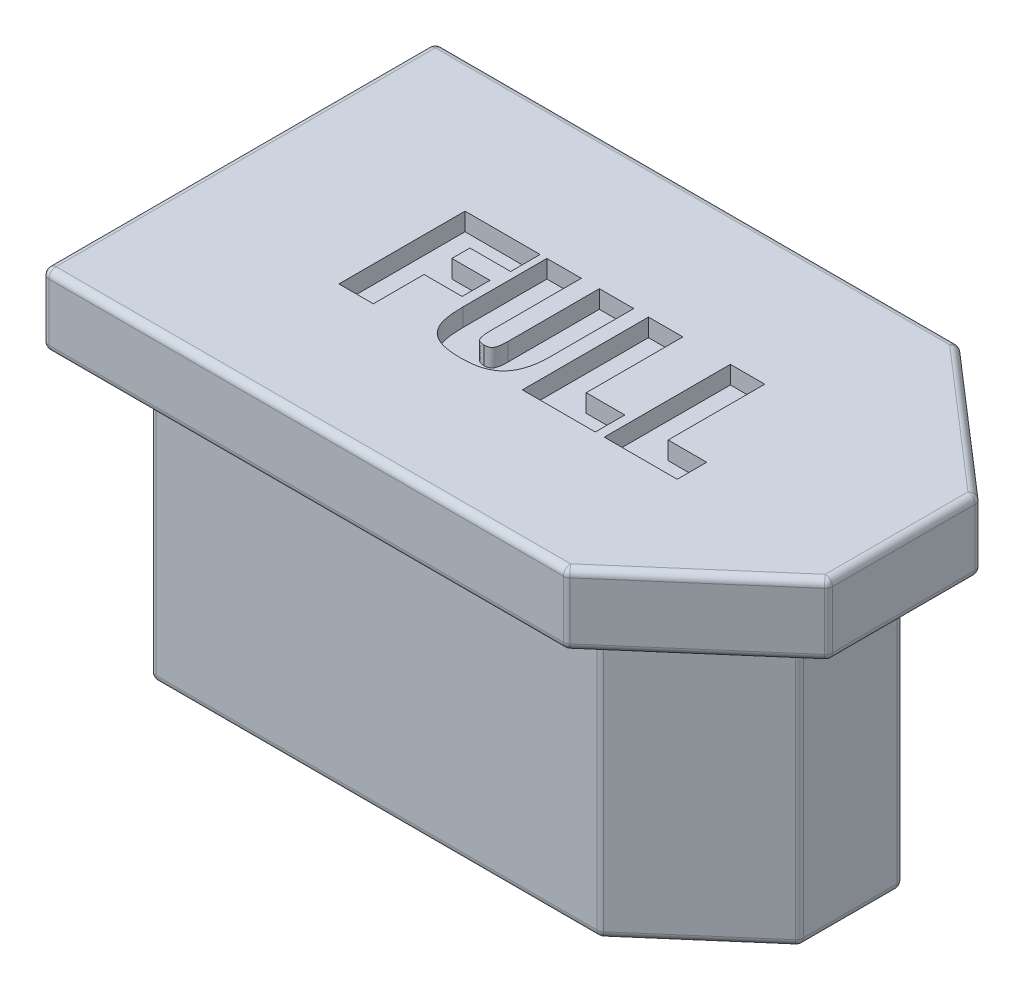
SolidWorks part; units mm, degrees
ref_plane "Front Plane" through (0, 0, 0) normal (0, 0, 1) x (1, 0, 0)
ref_plane "Top Plane" through (0, 0, 0) normal (0, 1, 0) x (1, 0, 0)
ref_plane "Right Plane" through (0, 0, 0) normal (1, 0, 0) x (0, 0, -1)
sketch "Sketch1" plane through (0, 0, 0) normal (0, 1, 0) x (1, 0, 0)
  line L0 (-7.8002, 4) -> (4.7998, 4)
  line L1 (4.7998, 4) -> (7.8002, 1.4)
  line L2 (7.8002, 1.4) -> (7.8002, -1.4)
  line L3 (7.8002, -1.4) -> (4.7998, -4)
  line L4 (4.7998, -4) -> (-7.8002, -4)
  line L5 (-7.8002, -4) -> (-7.8002, 4)
  line L6 (-7.8002, 0) -> (7.8002, 0) construction
  dimension "D1" = 8
  dimension "D2" = 12.6
  dimension "D3" = 139.09
  dimension "D4" = 2.8
extrude "Boss-Extrude1" add sketch "Sketch1" along normal mid plane 8
shell "Shell1" thickness 0.7
sketch "Sketch2" plane through (0, 4, 0) normal (0, 1, 0) x (1, 0, 0)
  line L0 (-7.8002, 4) -> (-7.8002, -4) construction
  line L1 (4.7998, 4) -> (-7.8002, 4) construction
  line L2 (7.8002, 1.4) -> (4.7998, 4) construction
  line L3 (7.8002, -1.4) -> (7.8002, 1.4) construction
  line L4 (4.7998, -4) -> (7.8002, -1.4) construction
  line L5 (-7.8002, -4) -> (4.7998, -4) construction
  line L6 (-7.8002, 4) -> (-7.8002, -4) construction
  line L7 (4.7998, 4) -> (-7.8002, 4) construction
  line L8 (7.8002, 1.4) -> (4.7998, 4) construction
  line L9 (7.8002, -1.4) -> (7.8002, 1.4) construction
  line L10 (4.7998, -4) -> (7.8002, -1.4) construction
  line L11 (-7.8002, -4) -> (4.7998, -4) construction
  line L12 (-9.3002, 5.5) -> (-9.3002, -5.5)
  line L13 (-9.3002, -5.5) -> (5.3593, -5.5)
  line L14 (5.3593, -5.5) -> (9.3002, -2.085)
  line L15 (9.3002, -2.085) -> (9.3002, 2.085)
  line L16 (9.3002, 2.085) -> (5.3593, 5.5)
  line L17 (5.3593, 5.5) -> (-9.3002, 5.5)
  dimension "D1" = 1.5
extrude "Boss-Extrude2" add sketch "Sketch2" along normal blind 2
sketch "Sketch4" plane through (0, -4, 0) normal (0, -1, 0) x (1, 0, 0)
  line L0 (-1.1002, -3.3) -> (-1.1002, -2.1)
  line L3 (4.5387, -3.3) -> (-7.1002, -3.3) construction
  line L5 (-1.1002, -2.1) -> (0.8998, -2.1)
  line L6 (0.8998, -2.1) -> (0.8998, -3.3)
  line L7 (-1.1002, -3.3) -> (0.8998, -3.3)
  dimension "D1" = 1.2
  dimension "D2" = 2
  dimension "D3" = 6
extrude "Boss-Extrude4" add sketch "Sketch4" against normal up to next
sketch "Sketch5" plane through (0, 4, 0) normal (0, -1, 0) x (1, 0, 0)
  line L0 (-0.6502, -2.1) -> (-0.6502, 1.9)
  line L1 (0.8998, -2.1) -> (-1.1002, -2.1) construction
  line L2 (-0.6502, 1.9) -> (0.4498, 1.9)
  line L3 (0.4498, 1.9) -> (0.4498, -2.1)
  line L4 (0.8998, -2.1) -> (-1.1002, -2.1) construction
  line L5 (0.4498, -2.1) -> (-0.6502, -2.1)
  line L6 (-0.1002, -2.1) -> (-0.1002, 1.9) construction
  dimension "D1" = 4
  dimension "D2" = 1.1
extrude "Cut-Extrude1" cut sketch "Sketch5" against normal blind 1
fillet "Fillet1" radius 0.2 78 edges at (4.5387, 0, -3.3) (7.1002, 0, -1.0803) (7.1002, 0, 1.0803) (4.5387, 0, 3.3) (-7.1002, 0, -3.3) (-1.1002, 0, -3.3) (-1.1002, 0, -2.1) (0.8998, 0, -2.1) (0.8998, 0, -3.3) (-7.1002, 0, 3.3) (0.8998, 4, -2.7) (0.8998, -4, -2.7) (2.7192, -4, -3.3) (-1.1002, 4, -2.7) (-1.1002, -4, -2.7) (-0.1002, 4, 1.9) (5.8195, -4, -2.1902) (-4.1002, -4, -3.3) (-0.1002, -4, -2.1) (-0.1002, 5, 1.9) (0.4498, 4.5, 1.9) (-0.6502, 4.5, 1.9) (0.4498, 5, -0.1) (-0.6502, 5, -0.1) (5.8195, 4, -2.1902) (2.7192, 4, -3.3) (-0.1002, 5, -2.1) (-4.1002, 4, -3.3) (7.1002, -4, 0) (7.1002, 4, 0) (-1.2808, -4, 3.3) (-1.2808, 4, 3.3) (5.8195, -4, 2.1902) (5.8195, 4, 2.1902) (-7.1002, -4, 0) (-7.1002, 4, 0) (-1.9705, 4, -5.5) (-9.3002, 4, 0) (-1.9705, 4, 5.5) (7.3297, 4, 3.7925) (9.3002, 4, 0) (7.3297, 4, -3.7925) (-1.9705, 6, -5.5) (-9.3002, 6, 0) (-1.9705, 6, 5.5) (7.3297, 6, 3.7925) (9.3002, 6, 0) (7.3297, 6, -3.7925) (5.3593, 5, -5.5) (9.3002, 5, -2.085) (9.3002, 5, 2.085) (5.3593, 5, 5.5) (-9.3002, 5, 5.5) (-9.3002, 5, -5.5) (-7.8002, -4, 0) (6.3, -4, 2.7) (7.8002, -4, 0) (6.3, -4, -2.7) (-1.5002, -4, -4) (-7.8002, 4, 0) (-1.5002, 4, 4) (6.3, 4, 2.7) (7.8002, 4, 0) (6.3, 4, -2.7) (-1.5002, 4, -4) (-7.8002, 0, -4) (4.7998, 0, -4) (7.8002, 0, -1.4) (7.8002, 0, 1.4) (4.7998, 0, 4) (-7.8002, 0, 4) (-1.5002, -4, 4)
sketch "Sketch6" plane through (0, 6, 0) normal (0, 1, 0) x (1, 0, 0)
  line L0 (-4.7296, 1.7632) -> (-2.6301, 1.7632)
  line L1 (-2.6301, 1.7632) -> (-2.6301, 0.9388)
  line L2 (-2.6301, 0.9388) -> (-3.7679, 0.9388)
  line L3 (-3.7679, 0.9388) -> (-3.7679, 0.4351)
  line L4 (-3.7679, 0.4351) -> (-2.7045, 0.4351)
  line L5 (-2.7045, 0.4351) -> (-2.7045, -0.3435)
  line L6 (-2.7045, -0.3435) -> (-3.7679, -0.3435)
  line L7 (-3.7679, -0.3435) -> (-3.7679, -1.7632)
  line L8 (-3.7679, -1.7632) -> (-4.7296, -1.7632)
  line L9 (-4.7296, -1.7632) -> (-4.7296, 1.7632)
  line L10 (-0.9743, 1.7632) -> (-0.0125, 1.7632)
  line L11 (-0.0125, 1.7632) -> (-0.0125, -0.5825)
  line L12 (-2.4398, -0.5825) -> (-2.4398, 1.7632)
  line L13 (-2.4398, 1.7632) -> (-1.478, 1.7632)
  line L14 (-1.478, 1.7632) -> (-1.478, -0.7843)
  line L15 (-0.9743, -0.7843) -> (-0.9743, 1.7632)
  line L16 (0.3997, 1.7632) -> (1.3614, 1.7632)
  line L17 (1.3614, 1.7632) -> (1.3614, -0.9388)
  line L18 (1.3614, -0.9388) -> (2.4398, -0.9388)
  line L19 (2.4398, -0.9388) -> (2.4398, -1.7632)
  line L20 (2.4398, -1.7632) -> (0.3997, -1.7632)
  line L21 (0.3997, -1.7632) -> (0.3997, 1.7632)
  line L22 (2.6895, 1.7632) -> (3.6512, 1.7632)
  line L23 (3.6512, 1.7632) -> (3.6512, -0.9388)
  line L24 (3.6512, -0.9388) -> (4.7296, -0.9388)
  line L25 (4.7296, -0.9388) -> (4.7296, -1.7632)
  line L26 (4.7296, -1.7632) -> (2.6895, -1.7632)
  line L27 (2.6895, -1.7632) -> (2.6895, 1.7632)
  line L28 (-4.7296, 0) -> (4.7296, 0) construction
  line L29 (0, 0) -> (0, -0.2478) construction
  spline S0 degree 3 poles (-0.0125, -0.5825) (-0.0131, -0.682) (-0.0189, -0.8273) (-0.05, -1.0125) (-0.0792, -1.1375) (-0.1188, -1.2525) (-0.1665, -1.3579) (-0.2242, -1.4526) (-0.2896, -1.5384) (-0.3657, -1.6142) (-0.4543, -1.6787) (-0.5541, -1.7342) (-0.6663, -1.778) (-0.7893, -1.8135) (-0.9767, -1.8459) (-1.1242, -1.8551) (-1.2261, -1.8548) knots 0 0 0 0 0.147092 0.213813 0.276818 0.336371 0.392915 0.447245 0.499697 0.551716 0.60508 0.661012 0.719774 0.782387 0.849635 1 1 1 1
  spline S1 degree 3 poles (-1.2261, -1.8548) (-1.3357, -1.8536) (-1.4935, -1.8483) (-1.6915, -1.8152) (-1.8181, -1.7837) (-1.9307, -1.7414) (-2.0305, -1.688) (-2.1187, -1.6249) (-2.195, -1.5509) (-2.2592, -1.4658) (-2.313, -1.3708) (-2.3562, -1.2652) (-2.3878, -1.149) (-2.4107, -1.0224) (-2.4346, -0.833) (-2.4391, -0.6846) (-2.4398, -0.5825) knots 0 0 0 0 0.1595 0.228771 0.291434 0.348949 0.403253 0.45542 0.506186 0.557166 0.609816 0.664557 0.722531 0.78463 0.851389 1 1 1 1
  spline S2 degree 3 poles (-1.478, -0.7843) (-1.477, -0.85) (-1.4759, -0.942) (-1.4539, -1.0517) (-1.4352, -1.1126) (-1.4038, -1.1606) (-1.3352, -1.206) (-1.2703, -1.213) (-1.2261, -1.2136) knots 0 0 0 0 0.343474 0.475215 0.581632 0.673592 0.767279 1 1 1 1
  spline S3 degree 3 poles (-1.2261, -1.2136) (-1.182, -1.213) (-1.117, -1.206) (-1.0484, -1.1606) (-1.017, -1.1126) (-0.9984, -1.0517) (-0.9764, -0.942) (-0.9753, -0.85) (-0.9743, -0.7843) knots 0 0 0 0 0.232721 0.326408 0.418368 0.524785 0.656526 1 1 1 1
extrude "Cut-Extrude2" cut sketch "Sketch6" against normal blind 0.5
